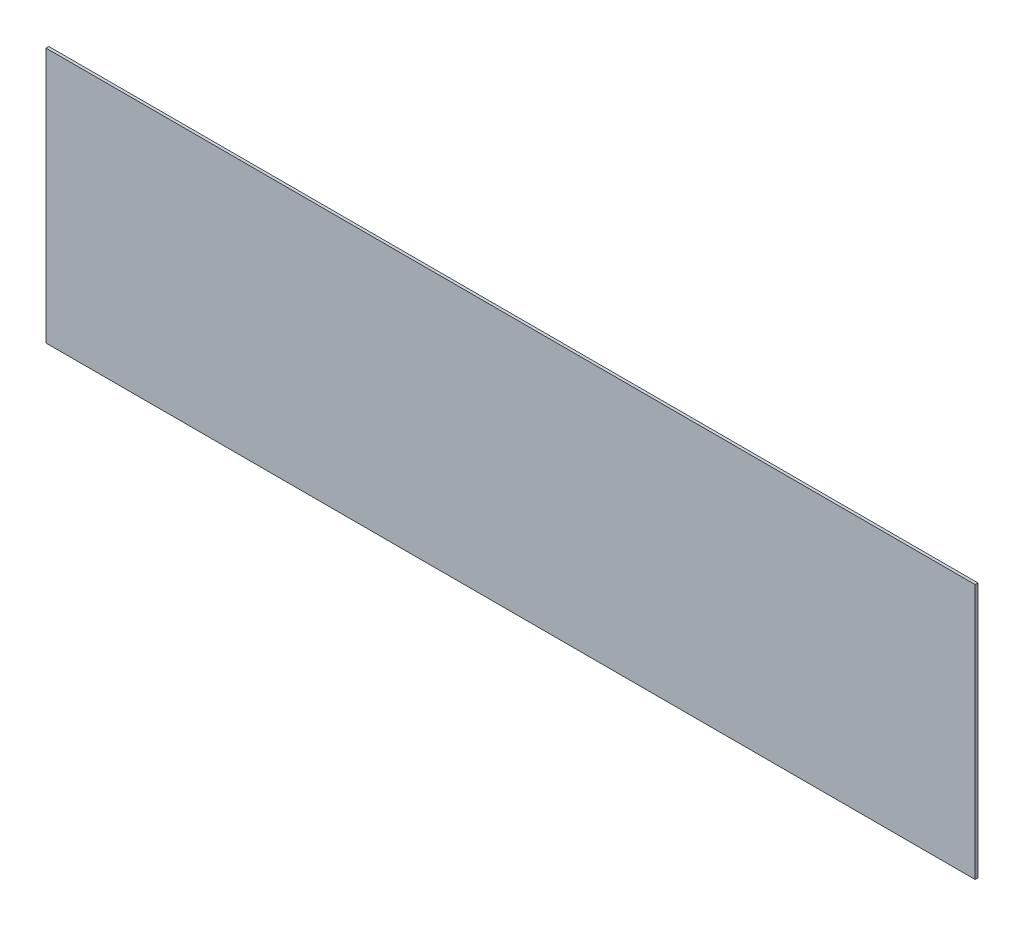
SolidWorks part; units mm, degrees
ref_plane "Front" through (0, 0, 0) normal (0, 0, 1) x (1, 0, 0)
ref_plane "Top" through (0, 0, 0) normal (0, 1, 0) x (1, 0, 0)
ref_plane "Right" through (0, 0, 0) normal (1, 0, 0) x (0, 0, -1)
sketch "草图1" plane through (0, 0, 0) normal (0, 0, 1) x (1, 0, 0)
  line L1 (-113.5033, 11.5656) -> (51.9967, 11.5656)
  line L2 (-113.5033, 11.5656) -> (-113.5033, -33.9344)
  line L3 (-113.5033, -33.9344) -> (51.9967, -33.9344)
  line L4 (51.9967, 11.5656) -> (51.9967, -33.9344)
  dimension "D1" = 165.5
  dimension "D2" = 45.5
extrude "凸台-拉伸1" add sketch "草图1" along normal blind 0.5
